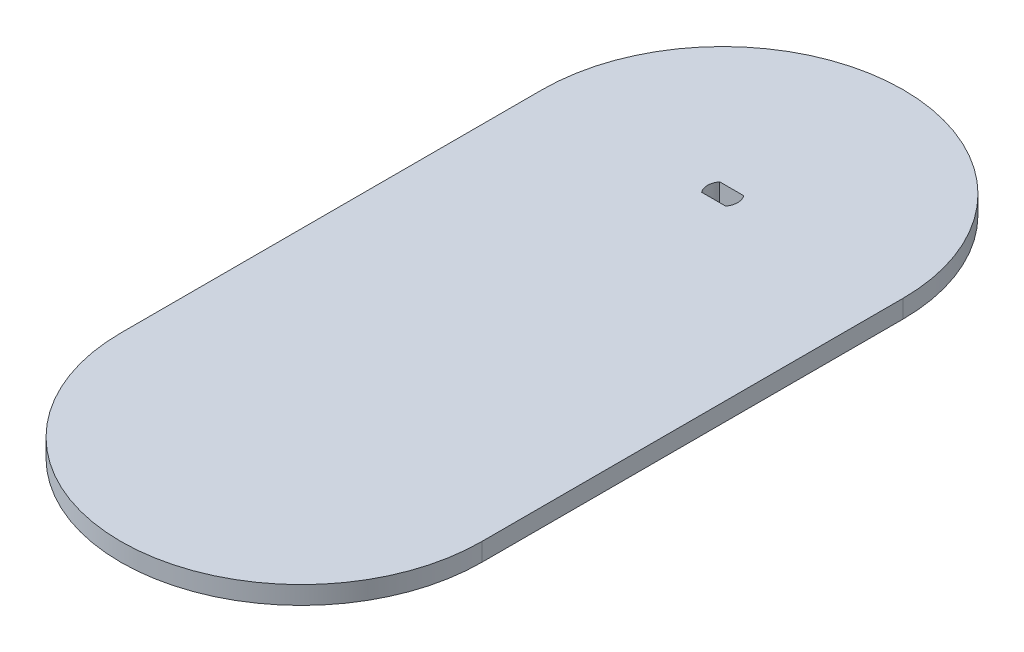
SolidWorks part; units mm, degrees
ref_plane "Front Plane" through (0, 0, 0) normal (0, 0, 1) x (1, 0, 0)
ref_plane "Top Plane" through (0, 0, 0) normal (0, 1, 0) x (1, 0, 0)
ref_plane "Right Plane" through (0, 0, 0) normal (1, 0, 0) x (0, 0, -1)
sketch "Sketch1" plane through (0, 0, 0) normal (0, 1, 0) x (1, 0, 0)
  line L0 (2, -1.5) -> (-2, -1.5)
  line L2 (-30, 0) -> (-30, -70)
  line L4 (30, 0) -> (30, -70)
  line L7 (2, 1.5) -> (-2, 1.5)
  arc A0 (30, 0) -> (-30, 0) centre (0, 0) ccw
  arc A1 (-30, -70) -> (30, -70) centre (0, -70) ccw
  arc A2 (-2, 1.5) -> (-2, -1.5) centre (0, 0) ccw
  arc A3 (2, -1.5) -> (2, 1.5) centre (0, 0) ccw
  dimension "D1" = 70
  dimension "D2" = 30
  dimension "D4" = 5
extrude "Boss-Extrude1" add sketch "Sketch1" along normal blind 3 contours A0 L2 A1 L4 | A2 L0 A3 L7
